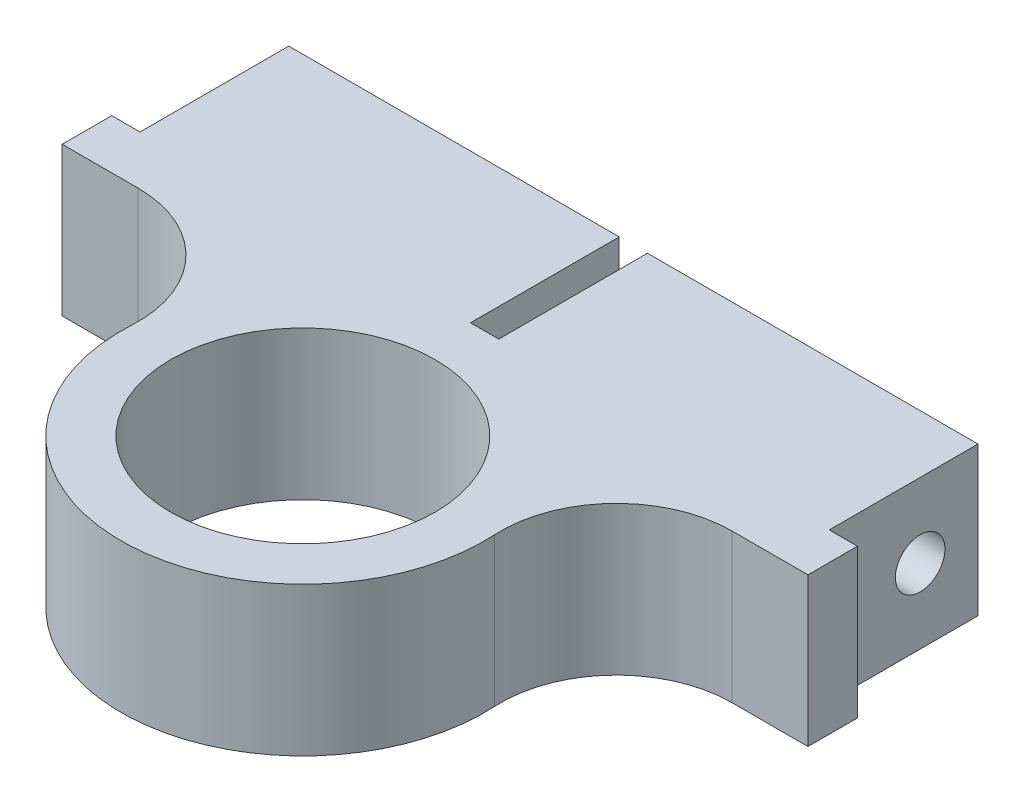
SolidWorks part; units mm, degrees
ref_plane "Front Plane" through (0, 0, 0) normal (0, 0, 1) x (1, 0, 0)
ref_plane "Top Plane" through (0, 0, 0) normal (0, 1, 0) x (1, 0, 0)
ref_plane "Right Plane" through (0, 0, 0) normal (1, 0, 0) x (0, 0, -1)
sketch "Sketch1" plane through (0, 0, 0) normal (0, 1, 0) x (1, 0, 0)
  line L0 (0, 0) -> (45.13, 0)
  line L1 (0, 0) -> (22.565, 0)
  line L2 (22.565, 0) -> (22.565, -8)
  line L3 (0, 0) -> (0, 7)
  line L4 (0, 7) -> (45.13, 7)
  line L5 (45.13, 7) -> (45.13, 0)
  circle A2 centre (22.565, -8) radius 11
  circle A3 centre (22.565, -8) radius 8
extrude "Boss-Extrude1" add sketch "Sketch1" along normal blind 10 contours A2 L0 L5 L4 L3 | L0 A2 L1 | A3 L1 A2 L0
fillet "Fillet1" radius 7 1 edges at (30.1148, 5, 0)
sketch "Sketch2" plane through (0, 10, 0) normal (0, 1, 0) x (1, 0, 0)
  line L0 (0, 7) -> (1.71, 7)
  line L1 (0, 7) -> (45.13, 7) construction
  line L2 (1.71, 7) -> (21.71, 7)
  line L3 (21.71, 7) -> (23.42, 7)
  line L4 (23.42, 7) -> (43.42, 7)
  line L5 (43.42, 7) -> (45.13, 7)
  line L6 (0, 0) -> (0, 3)
  line L7 (0, 0) -> (0, 7) construction
  line L8 (0, 3) -> (45.13, 3)
  line L9 (45.13, 7) -> (45.13, 0) construction
  line L10 (1.71, 7) -> (1.71, 3)
  line L11 (1.71, 3) -> (21.71, 3)
  line L12 (21.71, 3) -> (21.71, 7)
  line L13 (23.42, 7) -> (23.42, 3)
  line L14 (23.42, 3) -> (43.42, 3)
  line L15 (43.42, 3) -> (43.42, 7)
  line L16 (0, 7) -> (0, 3)
  line L17 (45.13, 3) -> (45.13, 7)
  line M7 (45.13, 0) -> (45.13, 7)
  line M8 (45.13, 7) -> (0, 7)
  line M9 (0, 7) -> (0, 0)
extrude "Cut-Extrude1" cut sketch "Sketch2" against normal blind 10 contours L10 L8 M8 M9 | L13 L12 L8 M8 | L15 L8 M7 M8
sketch "Sketch3" plane through (0, 0, -7) normal (0, 0, -1) x (-1, 0, 0)
  line L0 (-43.42, 0) -> (-23.42, 0) construction
  line L1 (-23.42, 0) -> (-23.42, 10) construction
  line L2 (-23.42, 10) -> (-43.42, 10) construction
  line L3 (-43.42, 10) -> (-43.42, 0) construction
  line L4 (-21.71, 0) -> (-1.71, 0) construction
  line L5 (-1.71, 0) -> (-1.71, 10) construction
  line L6 (-1.71, 10) -> (-21.71, 10) construction
  line L7 (-21.71, 10) -> (-21.71, 0) construction
  line L8 (-43.42, 0) -> (-23.42, 0)
  line L9 (-23.42, 0) -> (-23.42, 10)
  line L10 (-23.42, 10) -> (-43.42, 10)
  line L11 (-43.42, 10) -> (-43.42, 0)
  line L12 (-21.71, 0) -> (-1.71, 0)
  line L13 (-1.71, 0) -> (-1.71, 10)
  line L14 (-1.71, 10) -> (-21.71, 10)
  line L15 (-21.71, 10) -> (-21.71, 0)
extrude "Boss-Extrude2" add sketch "Sketch3" along normal blind 3
sketch "Sketch4" plane through (0, 10, 0) normal (0, 1, 0) x (1, 0, 0)
  line L13 (21.71, 3) -> (21.71, 10)
  line L14 (21.71, 10) -> (1.71, 10)
  line L15 (1.71, 10) -> (1.71, 3)
  line L16 (1.71, 3) -> (0, 3)
  line L17 (0, 3) -> (0, 0)
  line L18 (0, 0) -> (4.5928, 0)
  line L19 (40.5372, 0) -> (45.13, 0)
  line L20 (45.13, 0) -> (45.13, 3)
  line L21 (45.13, 3) -> (43.42, 3)
  line L22 (43.42, 3) -> (43.42, 10)
  line L23 (43.42, 10) -> (23.42, 10)
  line L24 (23.42, 10) -> (23.42, 3)
  line L25 (23.42, 3) -> (21.71, 3)
  line L26 (21.71, 3) -> (21.71, 10)
  line L27 (21.71, 10) -> (1.71, 10)
  line L28 (1.71, 10) -> (1.71, 3)
  line L29 (1.71, 3) -> (0, 3)
  line L30 (0, 3) -> (0, 0)
  line L31 (0, 0) -> (4.5928, 0)
  line L32 (40.5372, 0) -> (45.13, 0)
  line L33 (45.13, 0) -> (45.13, 3)
  line L34 (45.13, 3) -> (43.42, 3)
  line L35 (43.42, 3) -> (43.42, 10)
  line L36 (43.42, 10) -> (23.42, 10)
  line L37 (23.42, 10) -> (23.42, 3)
  line L38 (23.42, 3) -> (21.71, 3)
  arc A3 (11.582, -7.3889) -> (4.5928, 0) centre (4.5928, -7) ccw
  arc A4 (11.582, -7.3889) -> (33.548, -7.3889) centre (22.565, -8) ccw
  arc A5 (40.5372, 0) -> (33.548, -7.3889) centre (40.5372, -7) ccw
  arc A6 (11.582, -7.3889) -> (4.5928, 0) centre (4.5928, -7) ccw
  arc A7 (11.582, -7.3889) -> (33.548, -7.3889) centre (22.565, -8) ccw
  arc A8 (40.5372, 0) -> (33.548, -7.3889) centre (40.5372, -7) ccw
  dimension "D1" = 0
extrude "Cut-Extrude2" cut sketch "Sketch4" against normal blind 3
sketch "Sketch6" plane through (0, 0, -10) normal (0, 0, -1) x (-1, 0, 0)
  line L0 (-23.42, 0) -> (-23.42, 7) construction
  line L1 (-23.42, 7) -> (-43.42, 7) construction
  line L2 (-43.42, 7) -> (-43.42, 0) construction
  line L3 (-43.42, 0) -> (-23.42, 0) construction
  line L4 (-1.71, 0) -> (-1.71, 7) construction
  line L5 (-1.71, 7) -> (-21.71, 7) construction
  line L6 (-21.71, 7) -> (-21.71, 0) construction
  line L7 (-21.71, 0) -> (-1.71, 0) construction
  line L8 (-23.42, 0) -> (-23.42, 7)
  line L9 (-23.42, 7) -> (-43.42, 7)
  line L10 (-43.42, 7) -> (-43.42, 0)
  line L11 (-43.42, 0) -> (-23.42, 0)
  line L12 (-1.71, 0) -> (-1.71, 7)
  line L13 (-1.71, 7) -> (-21.71, 7)
  line L14 (-21.71, 7) -> (-21.71, 0)
  line L15 (-21.71, 0) -> (-1.71, 0)
extrude "Boss-Extrude3" add sketch "Sketch6" along normal blind 2
sketch "Sketch7" plane through (1.71, 0, 0) normal (-1, 0, 0) x (0, 0, 1)
  line L0 (-3, 0) -> (-3, 7)
  line L1 (-3, 7) -> (-3, 3.5)
  line L2 (-3, 3.5) -> (-8.5, 3.5)
  circle A0 centre (-8.5, 3.5) radius 1.5
extrude "Cut-Extrude5" cut sketch "Sketch7" against normal blind 44
sketch "Sketch8" plane through (0, 7, 0) normal (0, 1, 0) x (1, 0, 0)
  line L13 (23.42, 3) -> (21.71, 3)
  line L14 (21.71, 3) -> (21.71, 12)
  line L15 (21.71, 12) -> (1.71, 12)
  line L16 (1.71, 12) -> (1.71, 3)
  line L17 (1.71, 3) -> (0, 3)
  line L18 (0, 3) -> (0, 0)
  line L19 (0, 0) -> (4.5928, 0)
  line L20 (40.5372, 0) -> (45.13, 0)
  line L21 (45.13, 0) -> (45.13, 3)
  line L22 (45.13, 3) -> (43.42, 3)
  line L23 (43.42, 3) -> (43.42, 12)
  line L24 (43.42, 12) -> (23.42, 12)
  line L25 (23.42, 12) -> (23.42, 3)
  line L26 (23.42, 3) -> (21.71, 3)
  line L27 (21.71, 3) -> (21.71, 12)
  line L28 (21.71, 12) -> (1.71, 12)
  line L29 (1.71, 12) -> (1.71, 3)
  line L30 (1.71, 3) -> (0, 3)
  line L31 (0, 3) -> (0, 0)
  line L32 (0, 0) -> (4.5928, 0)
  line L33 (40.5372, 0) -> (45.13, 0)
  line L34 (45.13, 0) -> (45.13, 3)
  line L35 (45.13, 3) -> (43.42, 3)
  line L36 (43.42, 3) -> (43.42, 12)
  line L37 (43.42, 12) -> (23.42, 12)
  line L38 (23.42, 12) -> (23.42, 3)
  circle A0 centre (22.565, -8) radius 8 construction
  circle A1 centre (22.565, -8) radius 8
  arc A3 (11.582, -7.3889) -> (4.5928, 0) centre (4.5928, -7) ccw
  arc A4 (11.582, -7.3889) -> (33.548, -7.3889) centre (22.565, -8) ccw
  arc A5 (40.5372, 0) -> (33.548, -7.3889) centre (40.5372, -7) ccw
  arc A6 (11.582, -7.3889) -> (4.5928, 0) centre (4.5928, -7) ccw
  arc A7 (11.582, -7.3889) -> (33.548, -7.3889) centre (22.565, -8) ccw
  arc A8 (40.5372, 0) -> (33.548, -7.3889) centre (40.5372, -7) ccw
  dimension "D1" = 0
extrude "Boss-Extrude4" add sketch "Sketch8" along normal blind 1
sketch "Sketch9" plane through (0, 0, 0) normal (0, -1, 0) x (1, 0, 0)
  line L13 (1.71, -3) -> (1.71, -12)
  line L14 (1.71, -12) -> (21.71, -12)
  line L15 (21.71, -12) -> (21.71, -3)
  line L16 (21.71, -3) -> (23.42, -3)
  line L17 (23.42, -3) -> (23.42, -12)
  line L18 (23.42, -12) -> (43.42, -12)
  line L19 (43.42, -12) -> (43.42, -3)
  line L20 (43.42, -3) -> (45.13, -3)
  line L21 (45.13, -3) -> (45.13, 0)
  line L22 (45.13, 0) -> (40.5372, 0)
  line L23 (4.5928, 0) -> (0, 0)
  line L24 (0, 0) -> (0, -3)
  line L25 (0, -3) -> (1.71, -3)
  line L26 (1.71, -3) -> (1.71, -12)
  line L27 (1.71, -12) -> (21.71, -12)
  line L28 (21.71, -12) -> (21.71, -3)
  line L29 (21.71, -3) -> (23.42, -3)
  line L30 (23.42, -3) -> (23.42, -12)
  line L31 (23.42, -12) -> (43.42, -12)
  line L32 (43.42, -12) -> (43.42, -3)
  line L33 (43.42, -3) -> (45.13, -3)
  line L34 (45.13, -3) -> (45.13, 0)
  line L35 (45.13, 0) -> (40.5372, 0)
  line L36 (4.5928, 0) -> (0, 0)
  line L37 (0, 0) -> (0, -3)
  line L38 (0, -3) -> (1.71, -3)
  circle A0 centre (22.565, 8) radius 8 construction
  circle A1 centre (22.565, 8) radius 8
  arc A3 (33.548, 7.3889) -> (40.5372, 0) centre (40.5372, 7) ccw
  arc A4 (33.548, 7.3889) -> (11.582, 7.3889) centre (22.565, 8) ccw
  arc A5 (4.5928, 0) -> (11.582, 7.3889) centre (4.5928, 7) ccw
  arc A6 (33.548, 7.3889) -> (40.5372, 0) centre (40.5372, 7) ccw
  arc A7 (33.548, 7.3889) -> (11.582, 7.3889) centre (22.565, 8) ccw
  arc A8 (4.5928, 0) -> (11.582, 7.3889) centre (4.5928, 7) ccw
  dimension "D1" = 0
extrude "Boss-Extrude5" add sketch "Sketch9" along normal blind 1
